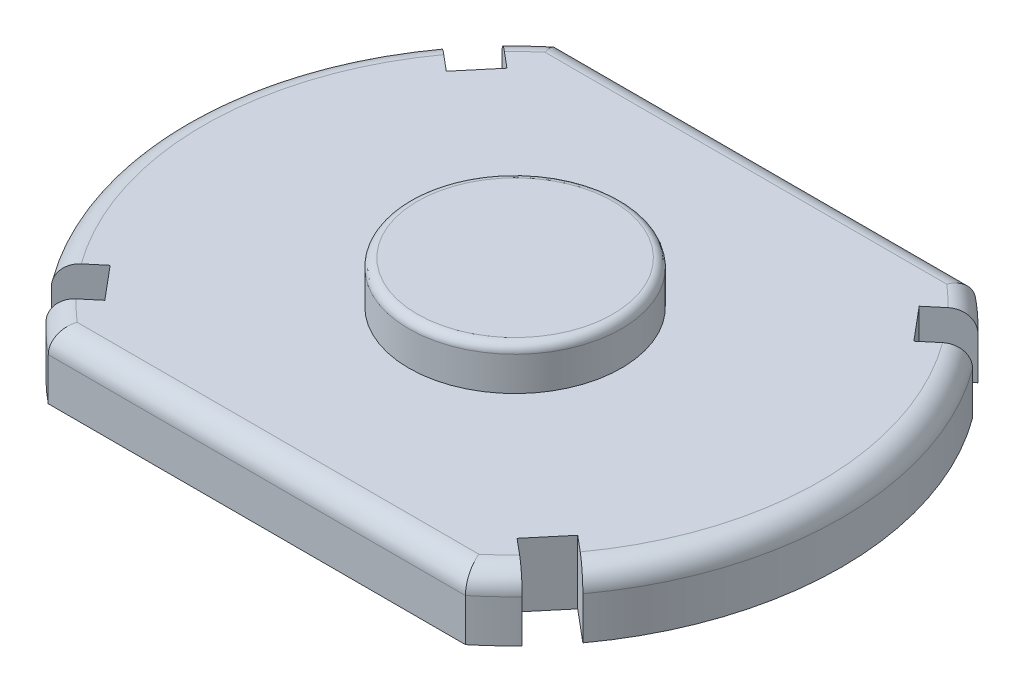
SolidWorks part; units mm, degrees
material "PUR"
ref_plane "Alzado" through (0, 0, 0) normal (0, 0, 1) x (1, 0, 0)
ref_plane "Planta" through (0, 0, 0) normal (0, 1, 0) x (1, 0, 0)
ref_plane "Vista lateral" through (0, 0, 0) normal (1, 0, 0) x (0, 0, -1)
sketch "Croquis2" plane through (0, 0, 0) normal (0, 1, 0) x (1, 0, 0)
  line L0 (-5.0146, 6.0358) -> (4.7962, 6.0358)
  line L1 (5.4896, 5.3945) -> (4.7376, 4.7635)
  line L2 (4.7962, -5.9642) -> (-5.0146, -5.9642)
  line L3 (5.063, 4.3758) -> (5.3883, 3.9881) construction
  line L4 (4.7376, 4.7635) -> (5.3883, 3.9881)
  line L5 (6.1403, 4.6191) -> (5.3883, 3.9881)
  line L6 (-5.708, -5.3228) -> (-4.956, -4.6918)
  line L7 (-6.3587, -4.5474) -> (-5.6067, -3.9164)
  line L8 (-4.956, -4.6918) -> (-5.6067, -3.9164)
  line L9 (-6.3587, 4.6191) -> (-5.6067, 3.9881)
  line L10 (-5.708, 5.3945) -> (-4.956, 4.7635)
  line L11 (-5.6067, 3.9881) -> (-4.956, 4.7635)
  line L12 (6.1403, -4.5474) -> (5.3883, -3.9164)
  line L13 (5.4896, -5.3228) -> (4.7376, -4.6918)
  line L14 (5.3883, -3.9164) -> (4.7376, -4.6918)
  arc A0 (-5.0146, 6.0358) -> (-5.708, 5.3945) centre (-0.1092, 0.0358) ccw
  arc A1 (4.7962, -5.9642) -> (5.4896, -5.3228) centre (-0.1092, 0.0358) ccw
  arc A2 (5.4896, 5.3945) -> (4.7962, 6.0358) centre (-0.1092, 0.0358) ccw
  arc A3 (6.1403, -4.5474) -> (6.1403, 4.6191) centre (-0.1092, 0.0358) ccw
  arc A4 (-5.708, -5.3228) -> (-5.0146, -5.9642) centre (-0.1092, 0.0358) ccw
  arc A5 (-6.3587, 4.6191) -> (-6.3587, -4.5474) centre (-0.1092, 0.0358) ccw
  point P19 (-0.1092, 0.0358)
  point P23 (-0.1092, 0.0358)
extrude "Saliente-Extruir1" add sketch "Croquis2" along normal blind 1.5
sketch "Croquis3" plane through (0, 1.5, 0) normal (0, 1, 0) x (1, 0, 0)
  circle A0 centre (0, 0) radius 2.5
extrude "Saliente-Extruir2" add sketch "Croquis3" along normal blind 1
fillet "Redondeo2" radius 0.5 8 edges at (5.1527, 1.5, -5.7258) (7.6408, 1.5, -0.0358) (-0.1092, 1.5, 5.9642) (-5.3711, 1.5, 5.6541) (-7.8592, 1.5, -0.0358) (-5.3711, 1.5, -5.7258) (-0.1092, 1.5, -6.0358) (5.1527, 1.5, 5.6541)
fillet "Redondeo3" radius 0.2 1 edges at (0, 2.5, 2.5)
